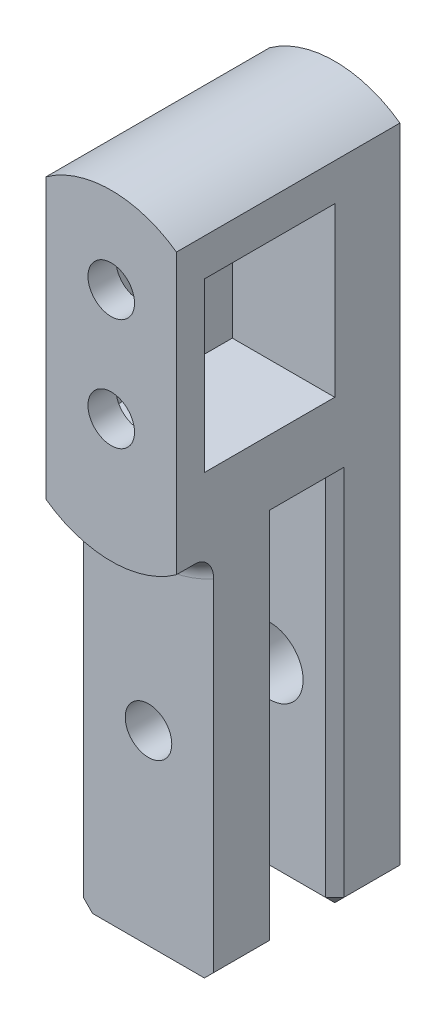
SolidWorks part; units mm, degrees
ref_plane "Front Plane" through (0, 0, 0) normal (0, 0, 1) x (1, 0, 0)
ref_plane "Top Plane" through (0, 0, 0) normal (0, 1, 0) x (1, 0, 0)
ref_plane "Right Plane" through (0, 0, 0) normal (1, 0, 0) x (0, 0, -1)
sketch "Sketch1" plane through (0, 0, 0) normal (0, 0, 1) x (1, 0, 0)
  line L1 (0, 0) -> (7, 0)
  line L2 (0, 0) -> (0, -35)
  line L3 (0, -35) -> (7, -35)
  line L4 (7, 0) -> (7, -35)
extrude "Boss-Extrude1" add sketch "Sketch1" along normal blind 3.5
sketch "Sketch2" plane through (0, 0, 3.5) normal (0, 0, 1) x (1, 0, 0)
  line L0 (0, 0) -> (0, -15)
  line L1 (0, 0) -> (0, -35) construction
  line L2 (0, -15) -> (7, -15)
  line L3 (7, -35) -> (7, 0) construction
  line L4 (7, -15) -> (7, 0)
  line L5 (7, 0) -> (0, 0)
extrude "Boss-Extrude2" add sketch "Sketch2" along normal blind 3
sketch "Sketch3" plane through (0, 0, 6.5) normal (0, 0, 1) x (1, 0, 0)
  line L1 (0, 0) -> (7, 0)
  line L2 (0, 0) -> (0, -35)
  line L3 (0, -35) -> (7, -35)
  line L4 (7, 0) -> (7, -35)
extrude "Boss-Extrude3" add sketch "Sketch3" along normal blind 3.5
sketch "Sketch4" plane through (0, 0, 10) normal (0, 0, 1) x (1, 0, 0)
  line L1 (0, 0) -> (7, 0)
  line L2 (0, 0) -> (0, -15)
  line L3 (0, -15) -> (7, -15)
  line L4 (7, 0) -> (7, -15)
extrude "Boss-Extrude4" add sketch "Sketch4" along normal blind 2
sketch "Sketch5" plane through (0, 0, 0) normal (-1, 0, 0) x (0, 0, 1)
  line L1 (3.5, -2) -> (10.5, -2)
  line L2 (3.5, -2) -> (3.5, -11)
  line L3 (3.5, -11) -> (10.5, -11)
  line L4 (10.5, -2) -> (10.5, -11)
  line L5 (12, 0) -> (0, 0) construction
  line L6 (12, 0) -> (12, -15) construction
  dimension "D1" = 9
  dimension "D2" = 7
  dimension "D3" = 1.5
  dimension "D4" = 2
extrude "Cut-Extrude1" cut sketch "Sketch5" against normal blind 5.5 from offset 1.5 offset against normal yes
sketch "Sketch6" plane through (5.5, 0, 0) normal (-1, 0, 0) x (0, 0, 1)
  line L0 (6.5, -2) -> (6.5, -11) construction
  line L1 (10.5, -2) -> (3.5, -2) construction
  line L2 (3.5, -11) -> (10.5, -11) construction
  line L3 (10.5, -11) -> (10.5, -2) construction
  line L4 (10.5, -2) -> (3.5, -2) construction
  circle A0 centre (6.5, -3.5) radius 0.75
  circle A1 centre (6.5, -9.5) radius 0.75
  circle A2 centre (6.5, -6.5) radius 0.75
  dimension "D2" = 1.5
  dimension "D4" = 4.5
  dimension "D1" = 4
  dimension "D3" = 1.5
extrude "Cut-Extrude2" cut sketch "Sketch6" along normal up to next
sketch "Sketch7" plane through (0, 0, 12) normal (0, 0, 1) x (1, 0, 0)
  line L0 (3.5, 0) -> (3.5, -15) construction
  line L1 (7, 0) -> (0, 0) construction
  line L2 (0, -15) -> (7, -15) construction
  line L3 (0, -2) -> (7, -2) construction
  line L4 (7, -15) -> (7, 0) construction
  circle A0 centre (3.5, -3.5) radius 1.25
  circle A1 centre (3.5, -9.5) radius 1.25
  dimension "D2" = 7.5
  dimension "D1" = 1.5
extrude "Cut-Extrude3" cut sketch "Sketch7" against normal up to next
sketch "Sketch9" plane through (0, 0, 12) normal (0, 0, 1) x (1, 0, 0)
  line L0 (0, 0) -> (7, 0)
  arc A0 (7, 0) -> (0, 0) centre (3.5, -4.8734) ccw
extrude "Boss-Extrude5" add sketch "Sketch9" against normal up to surface (12 mm away) up to face at (3.5, -17.5, 0)
sketch "Sketch10" plane through (0, 0, 12) normal (0, 0, 1) x (1, 0, 0)
  line L0 (0, -15) -> (7, -15)
  arc A0 (0, -15) -> (7, -15) centre (3.5, -10.1266) ccw
extrude "Boss-Extrude6" add sketch "Sketch10" against normal up to surface (2 mm away) up to face at (3.5, -25, 10)
chamfer "Chamfer1" distance 0.5 angle 45 12 edges at (0, -25, 3.5) (0, -15, 5) (0, -25, 6.5) (7, -35, 8.25) (0, -35, 8.25) (3.5, -35, 6.5) (0, -35, 1.75) (3.5, -35, 3.5) (7, -35, 1.75) (7, -25, 6.5) (7, -25, 3.5) (7, -15, 5)
sketch "Sketch11" plane through (0, 0, 10) normal (0, 0, 1) x (1, 0, 0)
  line L0 (3.5, -35) -> (3.5, -16.1266) construction
  line L1 (0.5, -35) -> (6.5, -35) construction
  arc A0 (0, -15) -> (7, -15) centre (3.5, -10.1266) ccw construction
  circle A1 centre (3.5, -25) radius 1.25
  dimension "D1" = 10
extrude "Cut-Extrude4" cut sketch "Sketch11" against normal up to next
sketch "Sketch12" plane through (0, 0, 0) normal (0, 0, -1) x (-1, 0, 0)
  line L0 (-3.5, -35) -> (-3.5, -18.8417) construction
  line L1 (-0.5, -35) -> (-6.5, -35) construction
  circle A0 centre (-3.5, -25) radius 1.8
  dimension "D1" = 10
extrude "Cut-Extrude5" cut sketch "Sketch12" against normal up to next
fillet "Fillet1" radius 1 1 edges at (3.5, -16.1266, 10)
